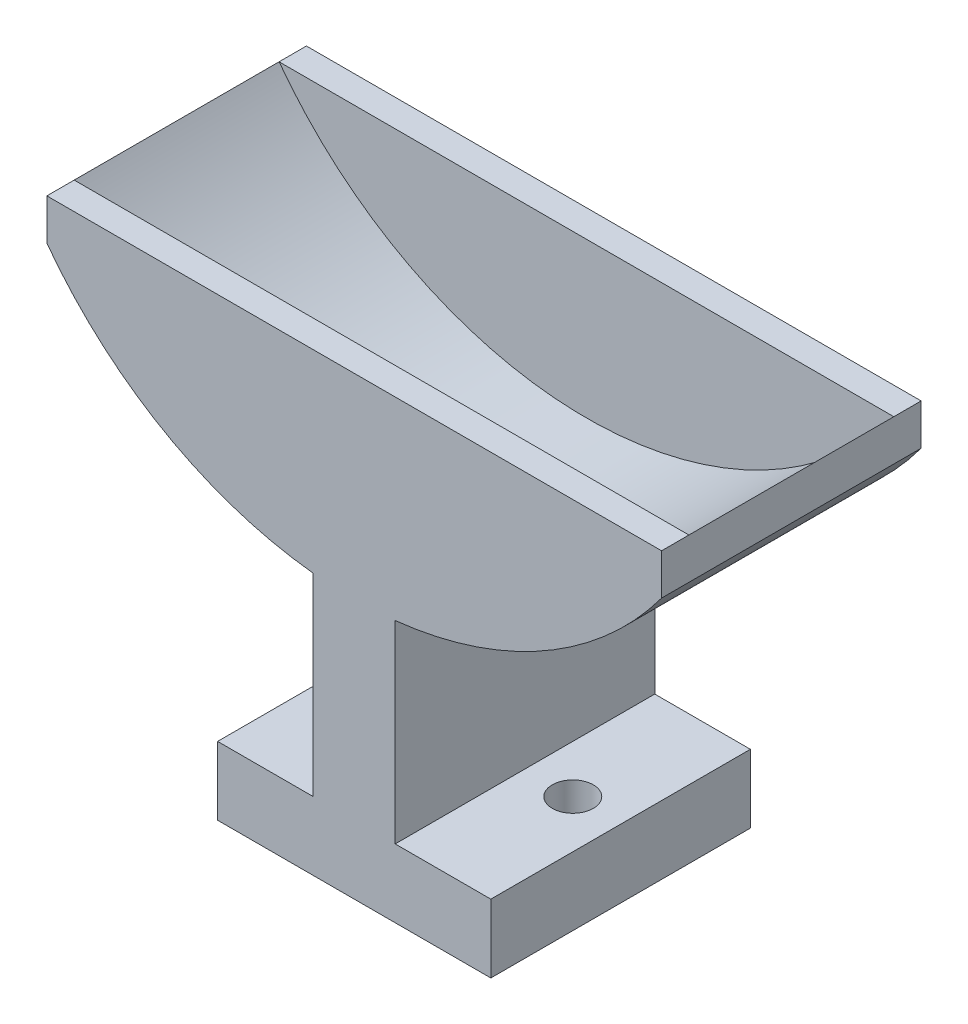
SolidWorks part; units mm, degrees
ref_plane "Front Plane" through (0, 0, 0) normal (0, 0, 1) x (1, 0, 0)
ref_plane "Top Plane" through (0, 0, 0) normal (0, 1, 0) x (1, 0, 0)
ref_plane "Right Plane" through (0, 0, 0) normal (1, 0, 0) x (0, 0, -1)
sketch "Sketch1" plane through (0, 0, 0) normal (0, 0, 1) x (1, 0, 0)
  line L0 (0, 0) -> (0, 5)
  line L1 (0, 5) -> (7, 5)
  line L2 (0, 0) -> (20, 0)
  line L3 (20, 0) -> (20, 5)
  line L4 (20, 5) -> (13, 5)
  line L5 (13, 5) -> (13, 19.1612)
  line L6 (7, 5) -> (7, 19.1612)
  line L7 (-12.5, 30.3342) -> (-12.5, 33.3342)
  line L8 (32.5, 30.3342) -> (32.5, 33.3342)
  circle A0 centre (10, 47) radius 28 construction
  arc A1 (32.5, 30.3342) -> (-12.5, 30.3342) centre (10, 47) cw
  arc A2 (-12.5, 33.3342) -> (32.5, 33.3342) centre (10, 50) ccw
  point P11 (10, 19)
  point P12 (10, 0)
  point P20 (32.5, 31.8342)
  dimension "D1" = 45
  dimension "D6" = 3
  dimension "D8" = 28
  dimension "D9" = 28
  dimension "D2" = 20
  dimension "D3" = 7
  dimension "D4" = 50
  dimension "D5" = 5
  dimension "D7" = 3
extrude "Boss-Extrude1" add sketch "Sketch1" along normal blind 19 contours L5 A1 L6 L1 L0 L2 L3 L4
ref_plane "Plane1" through (0, 33.3342, 0) normal (0, 1, 0) x (1, 0, 0)
sketch "Sketch2" plane through (0, 33.3342, 0) normal (0, 1, 0) x (1, 0, 0)
  line L0 (-12.5, -19) -> (-12.5, 0) construction
  line L1 (-12.5, 0) -> (32.5, 0) construction
  line L2 (32.5, 0) -> (32.5, -19) construction
  line L3 (32.5, -19) -> (-12.5, -19) construction
  line L4 (-12.5, -19) -> (32.5, 0) construction
  line L5 (-12.5, 0) -> (32.5, -19) construction
  line L6 (-12.5, -19) -> (-12.5, -17)
  line L7 (-12.5, -17) -> (32.5, -17)
  line L8 (32.5, -17) -> (32.5, -19)
  line L9 (32.5, -19) -> (-12.5, -19)
  line L10 (-12.5, -9.5) -> (32.5, -9.5) construction
  line L11 (32.5, -2) -> (32.5, 0)
  line L12 (-12.5, -2) -> (32.5, -2)
  line L13 (-12.5, 0) -> (-12.5, -2)
  line L14 (32.5, 0) -> (-12.5, 0)
  dimension "D1" = 15
extrude "Boss-Extrude2" add sketch "Sketch2" against normal up to surface up to face at (10, 27.6671, 9.5)
sketch "Sketch3" plane through (0, 5, 0) normal (0, 1, 0) x (1, 0, 0)
  line L0 (20, -19) -> (20, 0) construction
  line L1 (20, 0) -> (13, 0) construction
  line L2 (13, 0) -> (7, 0) construction
  line L3 (10, 0) -> (10, -19) construction
  circle A0 centre (16.5, -9.5) radius 1.5
  circle A1 centre (3.5, -9.5) radius 1.5
  point P7 (20, -9.5)
  point P11 (16.5, 0)
  dimension "D1" = 3
extrude "Cut-Extrude1" cut sketch "Sketch3" against normal up to surface (5 mm away) up to face at (10, 0, 9.5)
